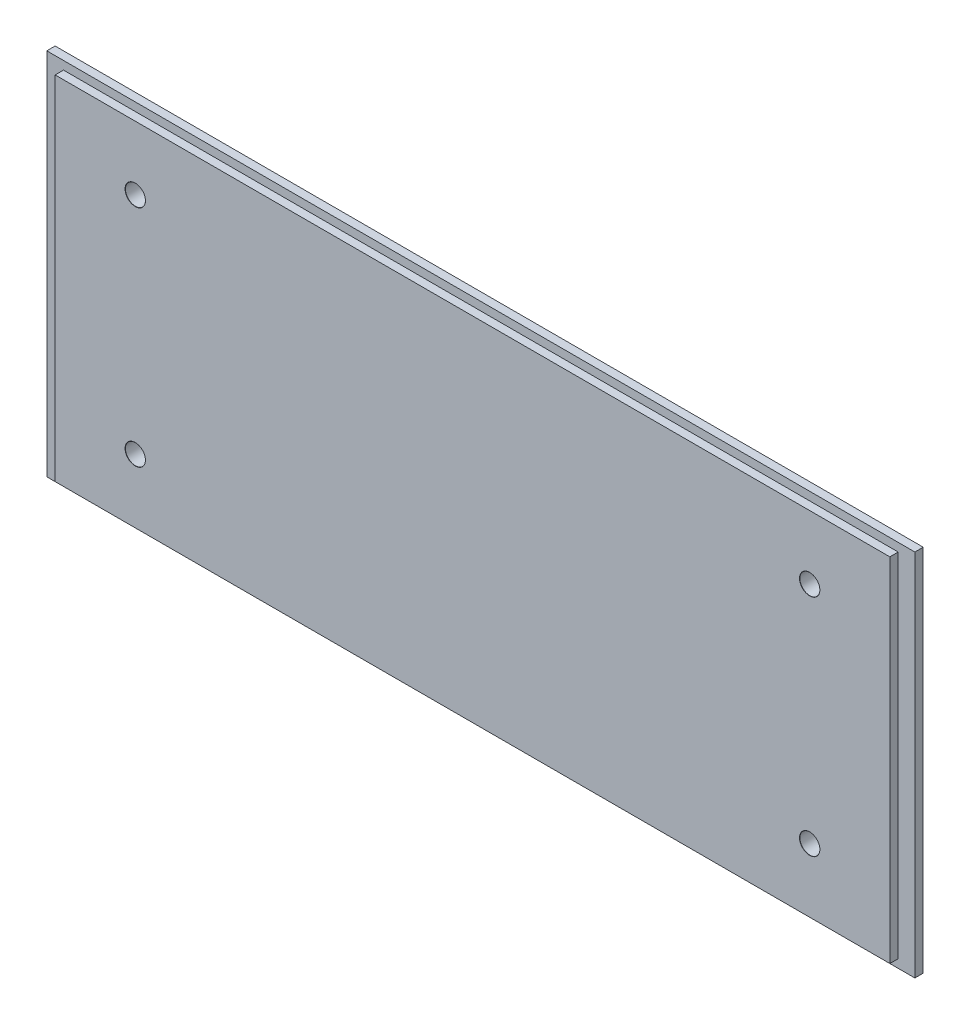
SolidWorks part; units mm, degrees
ref_plane "Plano frontal" through (0, 0, 0) normal (0, 0, 1) x (1, 0, 0)
ref_plane "Plano superior" through (0, 0, 0) normal (0, 1, 0) x (1, 0, 0)
ref_plane "Plano direito" through (0, 0, 0) normal (1, 0, 0) x (0, 0, -1)
sketch "Esboço1" plane through (0, 0, 0) normal (0, 0, 1) x (1, 0, 0)
  line L1 (-63.2916, 33.3513) -> (66.7084, 33.3513)
  line L2 (-63.2916, 33.3513) -> (-63.2916, -21.8987)
  line L3 (-63.2916, -21.8987) -> (66.7084, -21.8987)
  line L4 (66.7084, 33.3513) -> (66.7084, -21.8987)
  dimension "D1" = 130
  dimension "D2" = 55.25
extrude "Ressalto-extrusão1" add sketch "Esboço1" along normal blind 2.5
sketch "Esboço2" plane through (0, 0, 2.5) normal (0, 0, 1) x (1, 0, 0)
  line L0 (1.7084, 33.3513) -> (1.7084, -21.8987) construction
  line L1 (66.7084, 33.3513) -> (-63.2916, 33.3513) construction
  line L2 (-63.2916, -21.8987) -> (66.7084, -21.8987) construction
  line L11 (-54.581, 33.3513) -> (-54.581, -21.8987) construction
  line L13 (-63.2916, 33.3513) -> (66.7084, 33.3513)
  line L14 (-63.2916, 33.3513) -> (-63.2916, -21.8987)
  line L15 (-63.2916, -21.8987) -> (66.7084, -21.8987)
  line L16 (66.7084, 33.3513) -> (66.7084, -21.8987)
  line L17 (-60.7916, 32.1013) -> (64.2084, 32.1013)
  line L18 (-60.7916, 32.1013) -> (-60.7916, -20.6487)
  line L19 (-60.7916, -20.6487) -> (64.2084, -20.6487)
  line L20 (64.2084, 32.1013) -> (64.2084, -20.6487)
  dimension "D1" = 2.5
  dimension "D2" = 1.25
  dimension "D3" = 2.5
  dimension "D4" = 1.25
extrude "Corte-extrusão1" cut sketch "Esboço2" against normal blind 1.25
sketch "Esboço3" plane through (0, 0, 2.5) normal (0, 0, 1) x (1, 0, 0)
  line L0 (-48.7916, 32.1013) -> (-48.7916, -20.6487) construction
  line L1 (64.2084, 32.1013) -> (-60.7916, 32.1013) construction
  line L2 (-60.7916, -20.6487) -> (64.2084, -20.6487) construction
  line L3 (-60.7916, 32.1013) -> (-60.7916, -20.6487) construction
  line L4 (1.7084, 32.1013) -> (1.7084, -20.6487) construction
  line L5 (-60.7916, 5.7263) -> (1.7084, 5.7263) construction
  circle A0 centre (-48.7916, 22.5513) radius 1.5
  circle A1 centre (-48.7916, -11.0987) radius 1.5
  circle A2 centre (52.2084, -11.0987) radius 1.5
  circle A3 centre (52.2084, 22.5513) radius 1.5
  point P14 (-48.7916, 21.0513)
  dimension "D2" = 11.05
  dimension "D1" = 12
hole_wizard "Furos-guia com Ø3.0mm2" positions "Esboço4" profile "Esboço5" hole size "Ø3.0" standard "ISO" end condition through all
sketch "Esboço4" plane through (0, 0, 2.5) normal (0, 0, 1) x (1, 0, 0)
  point P0 (-48.7916, 22.5513)
  point P3 (-48.7916, -11.0987)
  point P6 (52.2084, -11.0987)
  point P9 (52.2084, 22.5513)
sketch "Esboço5" plane through (-48.7916, 22.5513, 2.5) normal (1, 0, 0) x (0, -1, 0)
  line L0 (0, 0) -> (0, 2.5)
  line L1 (0, 2.5) -> (1.5, 2.5)
  line L2 (1.5, 2.5) -> (1.5, 0.025)
  line L3 (1.5, 0.025) -> (1.525, 0)
  line L5 (1.525, 0) -> (0, 0)
  line L6 (-1.5, 0.025) -> (-1.525, 0) construction
  line L11 (0, -6.35) -> (0, 107.95) construction
  dimension "Thru Hole Dia." = 3
  dimension "Thru Hole Depth" = 2.5
  dimension "Near C'Sink Dia." = 3.05
  dimension "Near C'Sink Angle" = 90
